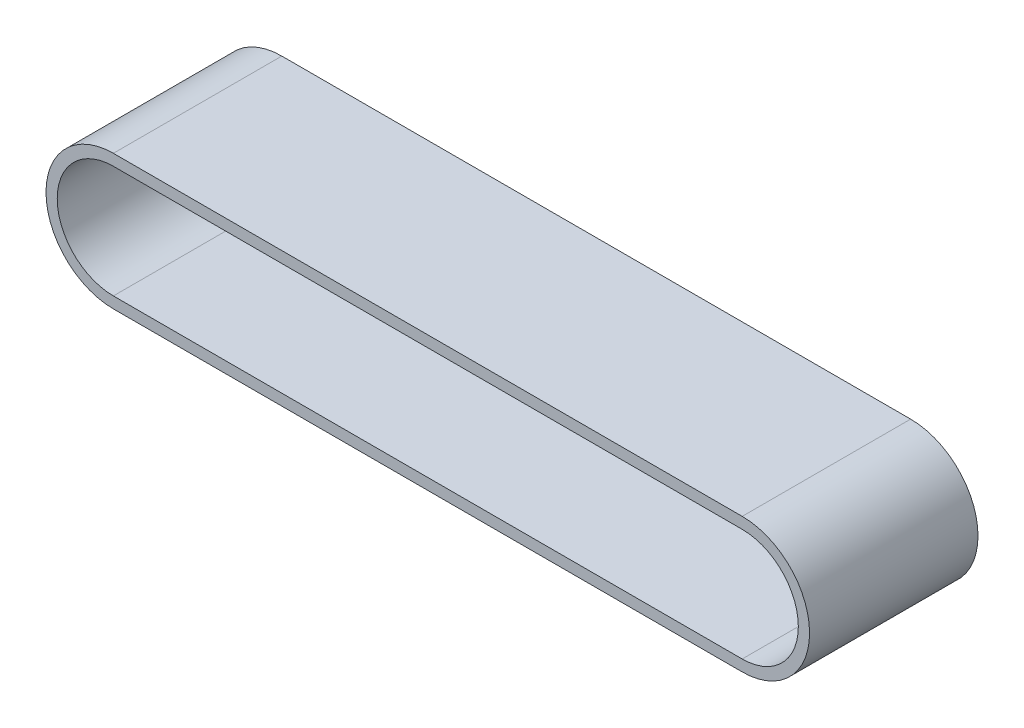
SolidWorks part; units mm, degrees
ref_plane "Front Plane" through (0, 0, 0) normal (0, 0, 1) x (1, 0, 0)
ref_plane "Top Plane" through (0, 0, 0) normal (0, 1, 0) x (1, 0, 0)
ref_plane "Right Plane" through (0, 0, 0) normal (1, 0, 0) x (0, 0, -1)
sketch "Sketch1" plane through (0, 0, 0) normal (0, 0, 1) x (1, 0, 0)
  line L0 (0, 0) -> (280, 0) construction
  line L1 (0, 25) -> (280, 25)
  line L2 (0, -25) -> (280, -25)
  line L3 (0, 0) -> (280, 0) construction
  line L4 (0, 30) -> (280, 30)
  line L5 (0, -30) -> (280, -30)
  arc A0 (0, 25) -> (0, -25) centre (0, 0) ccw
  arc A1 (280, -25) -> (280, 25) centre (280, 0) ccw
  arc A2 (0, 30) -> (0, -30) centre (0, 0) ccw
  arc A3 (280, -30) -> (280, 30) centre (280, 0) ccw
  point P3 (140, 0)
  point P11 (140, 0)
  dimension "D1" = 25
  dimension "D2" = 280
  dimension "D3" = 5
extrude "Boss-Extrude1" add sketch "Sketch1" along normal blind 75
sketch "Sketch2" plane through (0, 0, 0) normal (0, 0, -1) x (-1, 0, 0)
  line L0 (-280, 30) -> (-276, 30)
  line L1 (-280, 30) -> (0, 30) construction
  line L2 (-276, 30) -> (-276, 28)
  line L3 (-276, 28) -> (-270, 28)
  line L4 (-270, 28) -> (-270, 30)
  line L5 (-270, 30) -> (-266, 30)
  line L6 (-266, 30) -> (-266, 28)
  line L7 (-266, 28) -> (-260, 28)
  line L8 (-260, 28) -> (-260, 30)
  line L9 (-260, 30) -> (-256, 30)
  line L10 (-256, 30) -> (-256, 28)
  line L11 (-256, 28) -> (-250, 28)
  line L12 (-250, 28) -> (-250, 30)
  line L13 (-250, 30) -> (-246, 30)
  line L14 (-246, 30) -> (-246, 28)
  line L15 (-246, 28) -> (-240, 28)
  line L16 (-240, 28) -> (-240, 30)
  line L17 (-240, 30) -> (-236, 30)
  line L18 (-236, 30) -> (-236, 28)
  line L19 (-236, 28) -> (-230, 28)
  line L20 (-230, 28) -> (-230, 30)
  line L21 (-230, 30) -> (-226, 30)
  line L22 (-226, 30) -> (-226, 28)
  line L23 (-226, 28) -> (-220, 28)
  line L24 (-220, 28) -> (-220, 30)
  line L25 (-220, 30) -> (-216, 30)
  line L26 (-216, 30) -> (-216, 28)
  line L27 (-216, 28) -> (-210, 28)
  line L28 (-210, 28) -> (-210, 30)
  line L29 (-210, 30) -> (-206, 30)
  line L30 (-206, 30) -> (-206, 28)
  line L31 (-206, 28) -> (-200, 28)
  line L32 (-200, 28) -> (-200, 30)
  line L33 (-200, 30) -> (-196, 30)
  line L34 (-196, 30) -> (-196, 28)
  line L35 (-196, 28) -> (-190, 28)
  line L36 (-190, 28) -> (-190, 30)
  line L37 (-190, 30) -> (-186, 30)
  line L38 (-186, 30) -> (-186, 28)
  line L39 (-186, 28) -> (-180, 28)
  line L40 (-180, 28) -> (-180, 30)
  line L41 (-180, 30) -> (-176, 30)
  line L42 (-176, 30) -> (-176, 28)
  line L43 (-176, 28) -> (-170, 28)
  line L44 (-170, 28) -> (-170, 30)
  line L45 (-170, 30) -> (-166, 30)
  line L46 (-166, 30) -> (-166, 28)
  line L47 (-166, 28) -> (-160, 28)
  line L48 (-160, 28) -> (-160, 30)
  line L49 (-160, 30) -> (-156, 30)
  line L50 (-156, 30) -> (-156, 28)
  line L51 (-156, 28) -> (-150, 28)
  line L52 (-150, 28) -> (-150, 30)
  line L53 (-280, 30) -> (0, 30)
  line L54 (-150, 30) -> (-146, 30)
  line L55 (-146, 30) -> (-146, 28)
  line L56 (-146, 28) -> (-140, 28)
  line L57 (-140, 28) -> (-140, 30)
  line L58 (-140, 30) -> (-136, 30)
  line L59 (-136, 30) -> (-136, 28)
  line L60 (-136, 28) -> (-130, 28)
  line L61 (-130, 28) -> (-130, 30)
  line L62 (-130, 30) -> (-126, 30)
  line L63 (-126, 30) -> (-126, 28)
  line L64 (-126, 28) -> (-120, 28)
  line L65 (-120, 28) -> (-120, 30)
  line L66 (-120, 30) -> (-116, 30)
  line L67 (-116, 30) -> (-116, 28)
  line L68 (-116, 28) -> (-110, 28)
  line L69 (-110, 28) -> (-110, 30)
  line L70 (-110, 30) -> (-106, 30)
  line L71 (-106, 30) -> (-106, 28)
  line L72 (-106, 28) -> (-100, 28)
  line L73 (-100, 28) -> (-100, 30)
  line L74 (-100, 30) -> (-96, 30)
  line L75 (-96, 30) -> (-96, 28)
  line L76 (-96, 28) -> (-90, 28)
  line L77 (-90, 28) -> (-90, 30)
  dimension "D1" = 4
  dimension "D2" = 6
  dimension "D3" = 7
  dimension "2" = 2
  dimension "D4" = 13
sketch "Sketch3" plane through (0, 0, 0) normal (0, 0, -1) x (-1, 0, 0)
  line L0 (-280, -30) -> (-276, -30)
  line L1 (0, -30) -> (-280, -30) construction
  line L2 (-276, -30) -> (-276, -28)
  line L3 (-276, -28) -> (-270, -28)
  line L4 (-270, -28) -> (-270, -30)
  line L5 (-270, -30) -> (-266, -30)
  line L6 (-266, -30) -> (-266, -28)
  line L7 (-266, -28) -> (-260, -28)
  line L8 (-260, -28) -> (-260, -30)
  line L9 (-260, -30) -> (-256, -30)
  line L10 (-256, -30) -> (-256, -28)
  line L11 (-256, -28) -> (-250, -28)
  line L12 (-250, -28) -> (-250, -30)
  line L13 (-250, -30) -> (-246, -30)
  line L14 (-246, -30) -> (-246, -28)
  line L15 (-246, -28) -> (-240, -28)
  line L16 (-240, -28) -> (-240, -30)
  line L17 (-240, -30) -> (-236, -30)
  line L18 (-236, -30) -> (-236, -28)
  line L19 (-236, -28) -> (-230, -28)
  line L20 (-230, -28) -> (-230, -30)
  line L21 (-230, -30) -> (-226, -30)
  line L22 (-226, -30) -> (-226, -28)
  line L23 (-226, -28) -> (-220, -28)
  line L24 (-220, -28) -> (-220, -30)
  line L25 (-220, -30) -> (-216, -30)
  line L26 (-216, -30) -> (-216, -28)
  line L27 (-216, -28) -> (-210, -28)
  line L28 (-210, -28) -> (-210, -30)
  line L29 (-210, -30) -> (-206, -30)
  line L30 (-206, -30) -> (-206, -28)
  line L31 (-206, -28) -> (-200, -28)
  line L32 (-200, -28) -> (-200, -30)
  line L33 (-200, -30) -> (-196, -30)
  line L34 (-196, -30) -> (-196, -28)
  line L35 (-196, -28) -> (-190, -28)
  line L36 (-190, -28) -> (-190, -30)
  line L37 (-190, -30) -> (-186, -30)
  line L38 (-186, -30) -> (-186, -28)
  line L39 (-186, -28) -> (-180, -28)
  line L40 (-180, -28) -> (-180, -30)
  line L41 (-180, -30) -> (-176, -30)
  line L42 (-176, -30) -> (-176, -28)
  line L43 (-176, -28) -> (-170, -28)
  line L44 (-170, -28) -> (-170, -30)
  line L45 (-170, -30) -> (-166, -30)
  line L46 (-166, -30) -> (-166, -28)
  line L47 (-166, -28) -> (-160, -28)
  line L48 (-160, -28) -> (-160, -30)
  line L49 (-160, -30) -> (-156, -30)
  line L50 (-156, -30) -> (-156, -28)
  line L51 (-156, -28) -> (-150, -28)
  line L52 (-150, -28) -> (-150, -30)
  line L53 (-276, -30) -> (0, -30)
  line L54 (-150, -30) -> (-146, -30)
  line L55 (-146, -30) -> (-146, -28)
  line L56 (-146, -28) -> (-140, -28)
  line L57 (-140, -28) -> (-140, -30)
  line L58 (-140, -30) -> (-136, -30)
  line L59 (-136, -30) -> (-136, -28)
  line L60 (-136, -28) -> (-130, -28)
  line L61 (-130, -28) -> (-130, -30)
  line L62 (-130, -30) -> (-126, -30)
  line L63 (-126, -30) -> (-126, -28)
  line L64 (-126, -28) -> (-120, -28)
  line L65 (-120, -28) -> (-120, -30)
  line L66 (-120, -30) -> (-116, -30)
  line L67 (-116, -30) -> (-116, -28)
  line L68 (-116, -28) -> (-110, -28)
  line L69 (-110, -28) -> (-110, -30)
  line L70 (-110, -30) -> (-106, -30)
  line L71 (-106, -30) -> (-106, -28)
  line L72 (-106, -28) -> (-100, -28)
  line L73 (-100, -28) -> (-100, -30)
  line L74 (-100, -30) -> (-96, -30)
  line L75 (-96, -30) -> (-96, -28)
  line L76 (-96, -28) -> (-90, -28)
  line L77 (-90, -28) -> (-90, -30)
  dimension "D1" = 4
  dimension "D2" = 6
  dimension "D3" = 2
  dimension "D4" = 13
  dimension "D5" = 7
sketch "Sketch5" plane through (0, 0, 0) normal (0, 0, -1) x (-1, 0, 0)
  line L0 (-280, 30) -> (-280, 33)
  line L1 (-280, 0) -> (0, 0) construction
  line L2 (-140, -25) -> (-140, 25) construction
  line L3 (-280, 25) -> (0, 25) construction
  line L4 (0, 0) -> (0, 33) construction
  line L5 (3.76, 29.7634) -> (4.136, 32.7398)
  line L6 (7.4607, 29.0575) -> (8.2068, 31.9632)
  line L7 (11.0437, 27.8933) -> (12.1481, 30.6826)
  line L8 (14.4526, 26.2892) -> (15.8979, 28.9181)
  line L9 (17.6336, 24.2705) -> (19.3969, 26.6976)
  line L10 (20.5364, 21.8691) -> (22.5901, 24.056)
  line L11 (23.1154, 19.1227) -> (25.4269, 21.035)
  line L12 (25.3298, 16.0748) -> (27.8628, 17.6823)
  line L13 (27.1448, 12.7734) -> (29.8593, 14.0507)
  line L14 (28.5317, 9.2705) -> (31.3849, 10.1976)
  line L15 (29.4686, 5.6214) -> (32.4155, 6.1836)
  line L16 (29.9408, 1.8837) -> (32.9349, 2.0721)
  line L17 (29.9408, -1.8837) -> (32.9349, -2.0721)
  line L18 (29.4686, -5.6214) -> (32.4155, -6.1836)
  line L19 (28.5317, -9.2705) -> (31.3849, -10.1976)
  line L20 (27.1448, -12.7734) -> (29.8593, -14.0507)
  line L21 (25.3298, -16.0748) -> (27.8628, -17.6823)
  line L22 (23.1154, -19.1227) -> (25.4269, -21.035)
  line L23 (20.5364, -21.8691) -> (22.5901, -24.056)
  line L24 (17.6336, -24.2705) -> (19.3969, -26.6976)
  line L25 (-280, -30) -> (-280, -33)
  line L26 (-283.76, -29.7634) -> (-284.136, -32.7398)
  line L27 (-287.4607, -29.0575) -> (-288.2068, -31.9632)
  line L28 (-291.0437, -27.8933) -> (-292.1481, -30.6826)
  line L29 (-294.4526, -26.2892) -> (-295.8979, -28.9181)
  line L30 (-297.6336, -24.2705) -> (-299.3969, -26.6976)
  line L31 (-300.5364, -21.8691) -> (-302.5901, -24.056)
  line L32 (-303.1154, -19.1227) -> (-305.4269, -21.035)
  line L33 (-305.3298, -16.0748) -> (-307.8628, -17.6823)
  line L34 (-307.1448, -12.7734) -> (-309.8593, -14.0507)
  line L35 (-308.5317, -9.2705) -> (-311.3849, -10.1976)
  line L36 (-309.4686, -5.6214) -> (-312.4155, -6.1836)
  line L37 (-309.9408, -1.8837) -> (-312.9349, -2.0721)
  line L38 (-309.9408, 1.8837) -> (-312.9349, 2.0721)
  line L39 (-309.4686, 5.6214) -> (-312.4155, 6.1836)
  line L40 (-308.5317, 9.2705) -> (-311.3849, 10.1976)
  line L41 (-307.1448, 12.7734) -> (-309.8593, 14.0507)
  line L42 (-305.3298, 16.0748) -> (-307.8628, 17.6823)
  line L43 (-303.1154, 19.1227) -> (-305.4269, 21.035)
  line L44 (-300.5364, 21.8691) -> (-302.5901, 24.056)
  line L45 (-297.6336, 24.2705) -> (-299.3969, 26.6976)
  line L46 (-294.4526, 26.2892) -> (-295.8979, 28.9181)
  line L47 (-291.0437, 27.8933) -> (-292.1481, 30.6826)
  line L48 (-287.4607, 29.0575) -> (-288.2068, 31.9632)
  line L49 (-283.76, 29.7634) -> (-284.136, 32.7398)
  line L50 (-280, 0) -> (-280, 33) construction
  line L51 (-256.8846, 19.1227) -> (-254.5731, 21.035)
  line L52 (-254.6702, 16.0748) -> (-252.1372, 17.6823)
  line L53 (-252.8552, 12.7734) -> (-250.1407, 14.0507)
  line L54 (-251.4683, 9.2705) -> (-248.6151, 10.1976)
  line L55 (-250.5314, 5.6214) -> (-247.5845, 6.1836)
  line L56 (-250.0592, 1.8837) -> (-247.0651, 2.0721)
  line L57 (-250.0592, -1.8837) -> (-247.0651, -2.0721)
  line L58 (-250.5314, -5.6214) -> (-247.5845, -6.1836)
  line L59 (-251.4683, -9.2705) -> (-248.6151, -10.1976)
  line L60 (-252.8552, -12.7734) -> (-250.1407, -14.0507)
  line L61 (-254.6702, -16.0748) -> (-252.1372, -17.6823)
  line L62 (-256.8846, -19.1227) -> (-254.5731, -21.035)
  line L63 (-259.4636, -21.8691) -> (-257.4099, -24.056)
  line L64 (-262.3664, -24.2705) -> (-260.6031, -26.6976)
  line L65 (-265.5474, -26.2892) -> (-264.1021, -28.9181)
  line L66 (-268.9563, -27.8933) -> (-267.8519, -30.6826)
  line L67 (-272.5393, -29.0575) -> (-271.7932, -31.9632)
  line L68 (-276.24, -29.7634) -> (-275.864, -32.7398)
  line L69 (-276.24, 29.7634) -> (-275.864, 32.7398)
  line L70 (-272.5393, 29.0575) -> (-271.7932, 31.9632)
  line L71 (-268.9563, 27.8933) -> (-267.8519, 30.6826)
  line L72 (-265.5474, 26.2892) -> (-264.1021, 28.9181)
  line L73 (-262.3664, 24.2705) -> (-260.6031, 26.6976)
  line L74 (-259.4636, 21.8691) -> (-257.4099, 24.056)
  line L75 (14.4526, -26.2892) -> (15.8979, -28.9181)
  line L76 (11.0437, -27.8933) -> (12.1481, -30.6826)
  line L77 (7.4607, -29.0575) -> (8.2068, -31.9632)
  line L78 (3.76, -29.7634) -> (4.136, -32.7398)
  line L79 (0, -30) -> (0, -33)
  line L80 (0, 30) -> (0, 33)
  arc A0 (-280, 33) -> (-284.136, 32.7398) centre (-280, 0) ccw
  circle A1 centre (-280, 0) radius 30
  arc A2 (4.136, 32.7398) -> (8.2068, 31.9632) centre (0, 0) cw
  arc A3 (8.2068, 31.9632) -> (12.1481, 30.6826) centre (0, 0) cw
  arc A4 (12.1481, 30.6826) -> (15.8979, 28.9181) centre (0, 0) cw
  arc A5 (15.8979, 28.9181) -> (19.3969, 26.6976) centre (0, 0) cw
  arc A6 (19.3969, 26.6976) -> (22.5901, 24.056) centre (0, 0) cw
  arc A7 (22.5901, 24.056) -> (25.4269, 21.035) centre (0, 0) cw
  arc A8 (25.4269, 21.035) -> (27.8628, 17.6823) centre (0, 0) cw
  arc A9 (27.8628, 17.6823) -> (29.8593, 14.0507) centre (0, 0) cw
  arc A10 (29.8593, 14.0507) -> (31.3849, 10.1976) centre (0, 0) cw
  arc A11 (31.3849, 10.1976) -> (32.4155, 6.1836) centre (0, 0) cw
  arc A12 (32.4155, 6.1836) -> (32.9349, 2.0721) centre (0, 0) cw
  arc A13 (32.9349, 2.0721) -> (32.9349, -2.0721) centre (0, 0) cw
  arc A14 (32.9349, -2.0721) -> (32.4155, -6.1836) centre (0, 0) cw
  arc A15 (32.4155, -6.1836) -> (31.3849, -10.1976) centre (0, 0) cw
  arc A16 (31.3849, -10.1976) -> (29.8593, -14.0507) centre (0, 0) cw
  arc A17 (29.8593, -14.0507) -> (27.8628, -17.6823) centre (0, 0) cw
  arc A18 (27.8628, -17.6823) -> (25.4269, -21.035) centre (0, 0) cw
  arc A19 (25.4269, -21.035) -> (22.5901, -24.056) centre (0, 0) cw
  arc A20 (22.5901, -24.056) -> (19.3969, -26.6976) centre (0, 0) cw
  arc A21 (19.3969, -26.6976) -> (15.8979, -28.9181) centre (0, 0) cw
  arc A22 (15.8979, -28.9181) -> (12.1481, -30.6826) centre (0, 0) cw
  arc A23 (12.1481, -30.6826) -> (8.2068, -31.9632) centre (0, 0) cw
  arc A24 (8.2068, -31.9632) -> (4.136, -32.7398) centre (0, 0) cw
  arc A25 (4.136, -32.7398) -> (0, -33) centre (0, 0) cw
  arc A26 (-284.136, -32.7398) -> (-280, -33) centre (-280, 0) ccw
  arc A27 (-288.2068, -31.9632) -> (-284.136, -32.7398) centre (-280, 0) ccw
  arc A28 (-292.1481, -30.6826) -> (-288.2068, -31.9632) centre (-280, 0) ccw
  arc A29 (-295.8979, -28.9181) -> (-292.1481, -30.6826) centre (-280, 0) ccw
  arc A30 (-299.3969, -26.6976) -> (-295.8979, -28.9181) centre (-280, 0) ccw
  arc A31 (-302.5901, -24.056) -> (-299.3969, -26.6976) centre (-280, 0) ccw
  arc A32 (-305.4269, -21.035) -> (-302.5901, -24.056) centre (-280, 0) ccw
  arc A33 (-307.8628, -17.6823) -> (-305.4269, -21.035) centre (-280, 0) ccw
  arc A34 (-309.8593, -14.0507) -> (-307.8628, -17.6823) centre (-280, 0) ccw
  arc A35 (-311.3849, -10.1976) -> (-309.8593, -14.0507) centre (-280, 0) ccw
  arc A36 (-312.4155, -6.1836) -> (-311.3849, -10.1976) centre (-280, 0) ccw
  arc A37 (-312.9349, -2.0721) -> (-312.4155, -6.1836) centre (-280, 0) ccw
  arc A38 (-312.9349, 2.0721) -> (-312.9349, -2.0721) centre (-280, 0) ccw
  arc A39 (-312.4155, 6.1836) -> (-312.9349, 2.0721) centre (-280, 0) ccw
  arc A40 (-311.3849, 10.1976) -> (-312.4155, 6.1836) centre (-280, 0) ccw
  arc A41 (-309.8593, 14.0507) -> (-311.3849, 10.1976) centre (-280, 0) ccw
  arc A42 (-307.8628, 17.6823) -> (-309.8593, 14.0507) centre (-280, 0) ccw
  arc A43 (-305.4269, 21.035) -> (-307.8628, 17.6823) centre (-280, 0) ccw
  arc A44 (-302.5901, 24.056) -> (-305.4269, 21.035) centre (-280, 0) ccw
  arc A45 (-299.3969, 26.6976) -> (-302.5901, 24.056) centre (-280, 0) ccw
  arc A46 (-295.8979, 28.9181) -> (-299.3969, 26.6976) centre (-280, 0) ccw
  arc A47 (-292.1481, 30.6826) -> (-295.8979, 28.9181) centre (-280, 0) ccw
  arc A48 (-288.2068, 31.9632) -> (-292.1481, 30.6826) centre (-280, 0) ccw
  arc A49 (-284.136, 32.7398) -> (-288.2068, 31.9632) centre (-280, 0) ccw
  arc A50 (-275.864, 32.7398) -> (-280, 33) centre (-280, 0) ccw
  arc A51 (-254.5731, 21.035) -> (-257.4099, 24.056) centre (-280, 0) ccw
  arc A52 (-252.1372, 17.6823) -> (-254.5731, 21.035) centre (-280, 0) ccw
  arc A53 (-250.1407, 14.0507) -> (-252.1372, 17.6823) centre (-280, 0) ccw
  arc A54 (-248.6151, 10.1976) -> (-250.1407, 14.0507) centre (-280, 0) ccw
  arc A55 (-247.5845, 6.1836) -> (-248.6151, 10.1976) centre (-280, 0) ccw
  arc A56 (-247.0651, 2.0721) -> (-247.5845, 6.1836) centre (-280, 0) ccw
  arc A57 (-247.0651, -2.0721) -> (-247.0651, 2.0721) centre (-280, 0) ccw
  arc A58 (-247.5845, -6.1836) -> (-247.0651, -2.0721) centre (-280, 0) ccw
  arc A59 (-248.6151, -10.1976) -> (-247.5845, -6.1836) centre (-280, 0) ccw
  arc A60 (-250.1407, -14.0507) -> (-248.6151, -10.1976) centre (-280, 0) ccw
  arc A61 (-252.1372, -17.6823) -> (-250.1407, -14.0507) centre (-280, 0) ccw
  arc A62 (-254.5731, -21.035) -> (-252.1372, -17.6823) centre (-280, 0) ccw
  arc A63 (-257.4099, -24.056) -> (-254.5731, -21.035) centre (-280, 0) ccw
  arc A64 (-260.6031, -26.6976) -> (-257.4099, -24.056) centre (-280, 0) ccw
  arc A65 (-264.1021, -28.9181) -> (-260.6031, -26.6976) centre (-280, 0) ccw
  arc A66 (-267.8519, -30.6826) -> (-264.1021, -28.9181) centre (-280, 0) ccw
  arc A67 (-271.7932, -31.9632) -> (-267.8519, -30.6826) centre (-280, 0) ccw
  arc A68 (-275.864, -32.7398) -> (-271.7932, -31.9632) centre (-280, 0) ccw
  arc A69 (-280, -33) -> (-275.864, -32.7398) centre (-280, 0) ccw
  arc A70 (-271.7932, 31.9632) -> (-275.864, 32.7398) centre (-280, 0) ccw
  arc A71 (-267.8519, 30.6826) -> (-271.7932, 31.9632) centre (-280, 0) ccw
  arc A72 (-264.1021, 28.9181) -> (-267.8519, 30.6826) centre (-280, 0) ccw
  arc A73 (-260.6031, 26.6976) -> (-264.1021, 28.9181) centre (-280, 0) ccw
  arc A74 (-257.4099, 24.056) -> (-260.6031, 26.6976) centre (-280, 0) ccw
  circle A75 centre (0, 0) radius 30
  arc A76 (0, 33) -> (4.136, 32.7398) centre (0, 0) cw
  point P12 (-140, 0)
  dimension "D1" = 33
  dimension "D2" = 50
